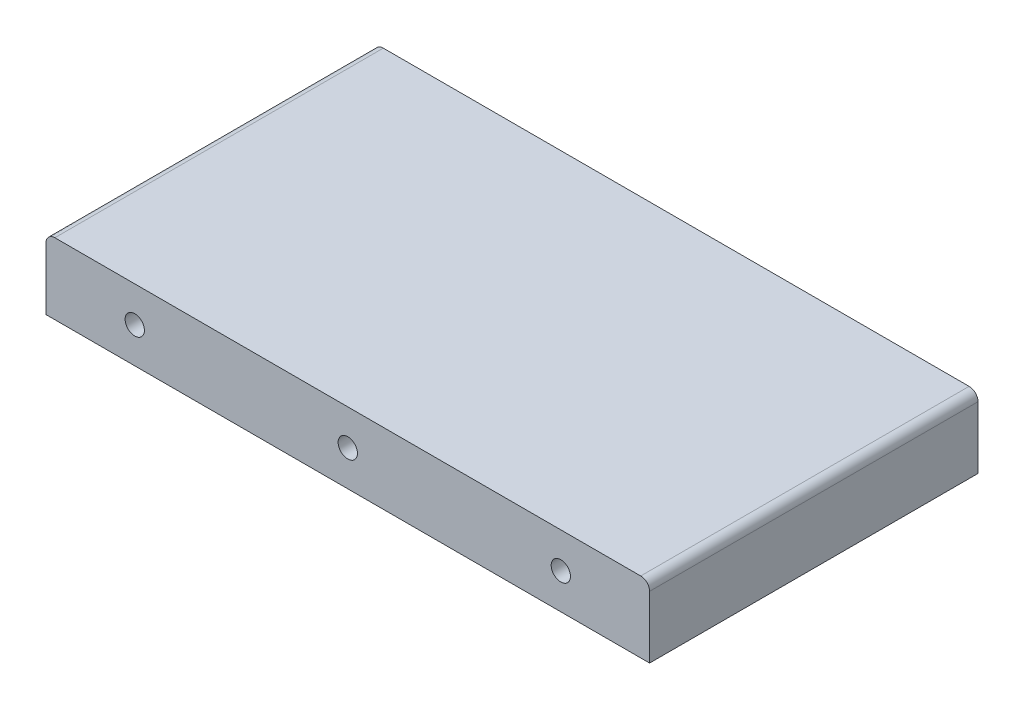
SolidWorks part; units mm, degrees
material "PE High Density"
ref_plane "Front Plane" through (0, 0, 0) normal (0, 0, 1) x (1, 0, 0)
ref_plane "Top Plane" through (0, 0, 0) normal (0, 1, 0) x (1, 0, 0)
ref_plane "Right Plane" through (0, 0, 0) normal (1, 0, 0) x (0, 0, -1)
sketch "Sketch1" plane through (0, 0, 0) normal (0, 0, 1) x (1, 0, 0)
  line L1 (-53.975, -6.35) -> (53.975, -6.35)
  line L2 (-53.975, -6.35) -> (-53.975, 6.35)
  line L3 (-53.975, 6.35) -> (53.975, 6.35)
  line L4 (53.975, -6.35) -> (53.975, 6.35)
  line L5 (-53.975, -6.35) -> (53.975, 6.35) construction
  line L6 (-53.975, 6.35) -> (53.975, -6.35) construction
  point P0 (0, 0)
  dimension "D1" = 107.95
  dimension "D2" = 12.7
extrude "Boss-Extrude1" add sketch "Sketch1" along normal mid plane 58.7375
hole_wizard "Tap Drill for #8-32 Tap1" positions "Sketch2" profile "Sketch4" hole size "#8-32" standard "ANSI Inch"
sketch "Sketch2" plane through (0, 0, 29.3687) normal (0, 0, 1) x (1, 0, 0)
  point P0 (-38.1, 0)
  point P2 (38.1, 0)
  point P7 (0, 0)
  dimension "D1" = 38.1
  dimension "D2" = 38.1
sketch "Sketch4" plane through (-38.1, 0, 29.3687) normal (1, 0, 0) x (0, -1, 0)
  line L0 (0, 0) -> (0, 20.0878)
  line L1 (0, 20.0878) -> (1.7272, 19.05)
  line L2 (1.7272, 19.05) -> (1.7272, 0)
  line L5 (1.7272, 0) -> (0, 0)
  line L10 (0, 20.0878) -> (-1.7272, 19.05) construction
  line L11 (0, -6.35) -> (0, 107.95) construction
  dimension "Hole Dia." = 3.4544
  dimension "Hole Depth" = 19.05
  dimension "Drill Angle" = 118
mirror "Mirror1" about plane through (0, 0, 0) normal (0, 0, 1) of "Tap Drill for #8-32 Tap1"
fillet "Fillet1" radius 1.5875 2 edges at (-53.975, 6.35, 0) (53.975, 6.35, 0)
equation "\"D2@Sketch2\"=\"D1@Sketch2\""
